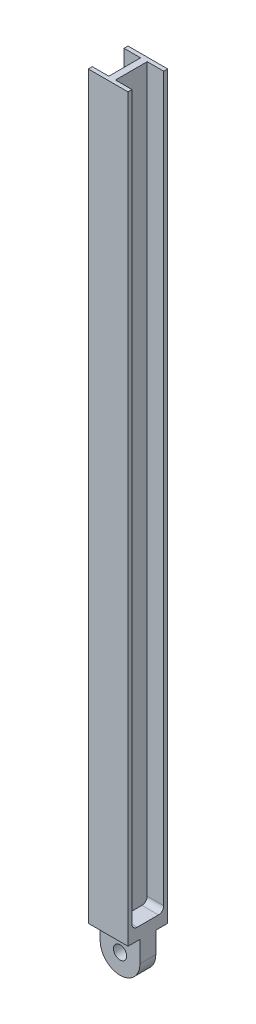
SolidWorks part; units mm, degrees
material "1060 Alloy"
ref_plane "Front Plane" through (0, 0, 0) normal (0, 0, 1) x (1, 0, 0)
ref_plane "Top Plane" through (0, 0, 0) normal (0, 1, 0) x (1, 0, 0)
ref_plane "Right Plane" through (0, 0, 0) normal (1, 0, 0) x (0, 0, -1)
sketch "Sketch1" plane through (0, 0, 0) normal (0, 1, 0) x (1, 0, 0)
  line L0 (-12.5, 3) -> (17.5, 3)
  line L1 (17.5, 3) -> (17.5, 0)
  line L2 (17.5, 0) -> (5, 0)
  line L3 (5, 0) -> (5, -24)
  line L4 (5, -24) -> (17.5, -24)
  line L5 (17.5, -24) -> (17.5, -27)
  line L6 (17.5, -27) -> (-12.5, -27)
  line L7 (-12.5, -27) -> (-12.5, -24)
  line L8 (-12.5, -24) -> (0, -24)
  line L9 (0, -24) -> (0, 0)
  line L10 (0, 0) -> (-12.5, 0)
  line L11 (-12.5, 0) -> (-12.5, 3)
  dimension "D1" = 30
  dimension "D2" = 30
  dimension "D3" = 3
  dimension "D4" = 24
  dimension "D5" = 30
  dimension "D6" = 3
  dimension "D7" = 5
  dimension "D8" = 12.5
  dimension "D9" = 12.5
  dimension "D10" = 12.5
  dimension "D11" = 24
  dimension "D12" = 12.5
extrude "Extrude4" add sketch "Sketch1" along normal blind 550
sketch "Sketch4" plane through (0, 0, 0) normal (0, -1, 0) x (1, 0, 0)
  line L12 (-12.5, 0) -> (-12.5, -3)
  line L13 (-12.5, -3) -> (17.5, -3)
  line L14 (17.5, -3) -> (17.5, 0)
  line L15 (17.5, 0) -> (5, 0)
  line L16 (5, 0) -> (5, 24)
  line L17 (5, 24) -> (17.5, 24)
  line L18 (17.5, 24) -> (17.5, 27)
  line L19 (17.5, 27) -> (-12.5, 27)
  line L20 (-12.5, 27) -> (-12.5, 24)
  line L21 (-12.5, 24) -> (0, 24)
  line L22 (0, 24) -> (0, 0)
  line L23 (0, 0) -> (-12.5, 0)
  line L24 (-12.5, 27) -> (-12.5, -3)
  line L25 (-12.5, -3) -> (17.5, -3)
  line L26 (17.5, -3) -> (17.5, 27)
  line L31 (17.5, 27) -> (-12.5, 27)
  dimension "D1" = 0
extrude "Extrude5" add sketch "Sketch4" along normal blind 40
sketch "Sketch5" plane through (0, -40, 0) normal (0, -1, 0) x (1, 0, 0)
  line L1 (-12.5, 6) -> (17.5, 6)
  line L2 (-12.5, 18) -> (17.5, 18)
  line L3 (17.5, 18) -> (17.5, 27)
  line L4 (-12.5, -3) -> (17.5, -3)
  line L5 (17.5, -3) -> (17.5, 27)
  line L6 (17.5, 27) -> (-12.5, 27)
  line L7 (-12.5, 27) -> (-12.5, -3)
  line L8 (-12.5, -3) -> (17.5, -3)
  line L9 (17.5, -3) -> (17.5, 6)
  line L10 (17.5, 27) -> (-12.5, 27)
  line L11 (-12.5, 27) -> (-12.5, 18)
  line L13 (-12.5, 6) -> (-12.5, -3)
  dimension "D2" = 9
  dimension "D3" = 9
  dimension "D4" = 12
  dimension "D1" = 0
extrude "Cut-Extrude2" cut sketch "Sketch5" against normal blind 31
sketch "Sketch6" plane through (0, 0, 18) normal (0, 0, 1) x (1, 0, 0)
  line L0 (-12.5, -9) -> (17.5, -9) construction
  line L1 (-12.5, -9) -> (-12.5, -40) construction
  circle A0 centre (2.5, -25) radius 5
  dimension "D3" = 15
  dimension "D1" = 10
  dimension "D2" = 16
extrude "Cut-Extrude3" cut sketch "Sketch6" against normal through all
sketch "Sketch7" plane through (0, 0, 18) normal (0, 0, 1) x (1, 0, 0)
  line L0 (-12.5, 573.5733) -> (17.5, 573.5733)
  line L4 (-12.5, -40) -> (17.5, -40)
  line L5 (17.5, -40) -> (17.5, -9)
  line L6 (17.5, -9) -> (-12.5, -9)
  line L7 (-12.5, -9) -> (-12.5, -40)
  line L9 (17.5, -25) -> (17.5, 573.5733)
  line L11 (-12.5, 573.5733) -> (-12.5, -25)
  arc A0 (-12.5, -25) -> (17.5, -25) centre (2.5, -25) ccw
  dimension "D2" = 30
  dimension "D1" = 0
extrude "Cut-Extrude4" cut sketch "Sketch7" against normal through all flip side to cut
fillet "Fillet2" radius 4 2 edges
fillet "Fillet3" radius 4 2 edges
